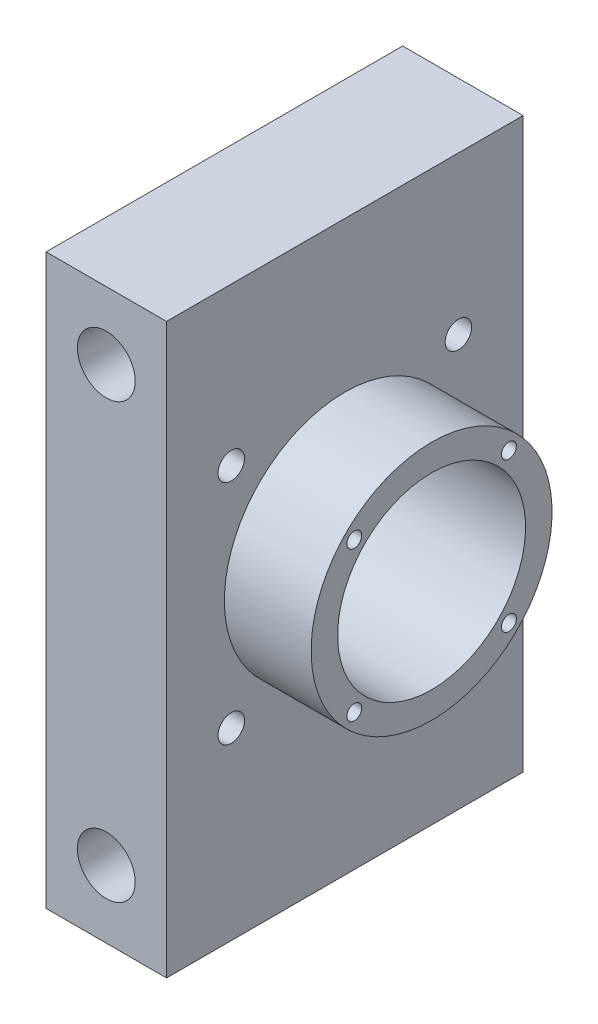
SolidWorks part; units mm, degrees
ref_plane "Front Plane" through (0, 0, 0) normal (0, 0, 1) x (1, 0, 0)
ref_plane "Top Plane" through (0, 0, 0) normal (0, 1, 0) x (1, 0, 0)
ref_plane "Right Plane" through (0, 0, 0) normal (1, 0, 0) x (0, 0, -1)
sketch "Sketch1" plane through (0, 0, 0) normal (0, 0, 1) x (1, 0, 0)
  line L0 (0, 100) -> (0, 85.5)
  line L1 (0, 100) -> (-25, 100)
  line L2 (-25, 100) -> (-25, 0)
  line L3 (-25, 0) -> (0, 0)
  line L4 (6.5355, 52.7939) -> (-58.3851, 52.7939) construction
  line L5 (0, 85.5) -> (-5.5, 85.5)
  line L6 (-5.5, 85.5) -> (-5.5, 92.242)
  line L7 (-5.5, 92.242) -> (-11, 92.242)
  line L8 (-11, 92.242) -> (-11, 13.3459)
  line L9 (-5.5, 20.0879) -> (-5.5, 13.3459)
  line L10 (-5.5, 13.3459) -> (-11, 13.3459)
  line L11 (0, 5.5879) -> (0, 20.0879)
  line L12 (0, 20.0879) -> (-5.5, 20.0879)
  line L13 (0, 0) -> (0, 5.5879)
  point P15 (-11, 52.7939)
  dimension "D1" = 100
  dimension "D2" = 25
  dimension "D3" = 5.5
  dimension "D4" = 5.5
  dimension "D5" = 14.5
extrude "Boss-Extrude1" add sketch "Sketch1" along normal blind 320
sketch "Sketch2" plane through (0, 0, 0) normal (0, 0, -1) x (-1, 0, 0)
  line L0 (0, 100) -> (0, 0)
  line L1 (0, 0) -> (25, 0)
  line L2 (25, 0) -> (25, 100)
  line L3 (25, 100) -> (0, 100)
extrude "Boss-Extrude2" add sketch "Sketch2" along normal blind 50
sketch "Sketch3" plane through (0, 0, 0) normal (1, 0, 0) x (0, 0, -1)
  line L0 (0, 52.7939) -> (50, 52.7939) construction
  line L1 (0, 13.3459) -> (0, 92.242) construction
  line L2 (25, 110.2506) -> (25, -20.6618) construction
  circle A0 centre (25, 52.7939) radius 5
  dimension "D2" = 10
  dimension "D1" = 50
extrude "Cut-Extrude1" cut sketch "Sketch3" against normal through all both and the other way through all
sketch "Sketch4" plane through (0, 100, 0) normal (0, 1, 0) x (1, 0, 0)
  line L0 (-25, -320) -> (-25, -339.2114)
  line L1 (-25, -339.2114) -> (125, -339.2114)
  line L2 (125, -339.2114) -> (125, -320)
  line L3 (125, -320) -> (-25, -320)
  dimension "D1" = 150
extrude "Boss-Extrude3" add sketch "Sketch4" against normal up to surface (100 mm away) up to face at (-12.5, 0, 135)
sketch "Sketch5" plane through (0, 0, 0) normal (0, 1, 0) x (1, 0, 0)
  line L0 (125, -339.2114) -> (125, -209.2114)
  line L1 (125, -209.2114) -> (140, -209.2114)
  line L2 (140, -209.2114) -> (140, -339.2114)
  line L3 (140, -339.2114) -> (127.2454, -339.2114)
  line L4 (125, -339.2114) -> (140, -339.2114)
  dimension "D1" = 130
  dimension "D2" = 15
extrude "Boss-Extrude4" add sketch "Sketch5" along normal up to surface (100 mm away) contours L0 L4 L3 L2 L1 up to face at (33.3333, 100, 203.0705)
sketch "Sketch6" plane through (-25, 0, 0) normal (-1, 0, 0) x (0, 0, 1)
  line L1 (-46.05, 73.8439) -> (-3.95, 73.8439)
  line L2 (-46.05, 73.8439) -> (-46.05, 31.7439)
  line L3 (-46.05, 31.7439) -> (-3.95, 31.7439)
  line L4 (-3.95, 73.8439) -> (-3.95, 31.7439)
  line L5 (-46.05, 73.8439) -> (-3.95, 31.7439) construction
  line L6 (-46.05, 31.7439) -> (-3.95, 73.8439) construction
  point P0 (-25, 52.7939)
  dimension "D1" = 42.1
  dimension "D2" = 42.1
extrude "Cut-Extrude2" cut sketch "Sketch6" against normal blind 10
sketch "Sketch7" plane through (-15, 0, 0) normal (-1, 0, 0) x (0, 0, 1)
  circle A0 centre (-25, 52.7939) radius 11
  dimension "D1" = 22
extrude "Cut-Extrude3" cut sketch "Sketch7" against normal blind 2
sketch "Sketch8" plane through (-25, 0, 0) normal (-1, 0, 0) x (0, 0, 1)
  circle A0 centre (-25, 52.7939) radius 11
extrude "Cut-Extrude4" cut sketch "Sketch8" against normal through all both and the other way through all
sketch "Sketch10" plane through (0, 0, 0) normal (1, 0, 0) x (0, 0, -1)
  circle A0 centre (25, 52.7939) radius 11
  circle A1 centre (25, 52.7939) radius 25
extrude "Boss-Extrude5" add sketch "Sketch10" along normal blind 18
sketch "Sketch11" plane through (0, 0, 0) normal (0, 1, 0) x (1, 0, 0)
  line L0 (-25, -339.2114) -> (-25, -218.2114)
  line L1 (-25, -339.2114) -> (-25, 50) construction
  line L2 (-25, -218.2114) -> (83.7284, -218.2114)
  line L3 (83.7284, -218.2114) -> (83.7284, -190.051)
  line L4 (83.7284, -190.051) -> (162.6734, -190.051)
  line L5 (162.6734, -190.051) -> (162.6734, -339.2114)
  line L6 (162.6734, -339.2114) -> (-25, -339.2114)
  dimension "D1" = 121
extrude "Cut-Extrude6" cut sketch "Sketch11" against normal through all and the other way through all
sketch "Sketch12" plane through (0, 0, 0) normal (0, 1, 0) x (1, 0, 0)
  line L0 (-25, -218.2114) -> (125, -218.2114)
  line L1 (125, -218.2114) -> (125, -203.2114)
  line L2 (125, -203.2114) -> (-25, -203.2114)
  line L3 (-25, -218.2114) -> (-25, 50) construction
  line L4 (-25, -203.2114) -> (-25, -218.2114)
  line L5 (125, -218.2114) -> (140, -218.2114)
  line L6 (140, -218.2114) -> (140, -118.2114)
  line L7 (140, -118.2114) -> (125, -118.2114)
  line L8 (125, -118.2114) -> (125, -203.2114)
  dimension "D1" = 150
  dimension "D2" = 15
  dimension "D3" = 100
  dimension "D4" = 15
extrude "Boss-Extrude6" add sketch "Sketch12" along normal up to surface (100 mm away) contours L2 L4 L0 L1 | L7 L8 L1 L5 L6 up to face at (-12.5, 100, 84.1057)
sketch "Sketch13" plane through (0, 0, 0) normal (0, 1, 0) x (1, 0, 0)
  line L0 (-25, -218.2114) -> (-25, -223.2114)
  line L1 (-25, -223.2114) -> (140, -223.2114)
  line L2 (140, -223.2114) -> (140, -218.2114)
  line L3 (-25, -218.2114) -> (140, -218.2114)
  dimension "D1" = 5
extrude "Boss-Extrude7" add sketch "Sketch13" along normal up to surface (100 mm away) up to face at (60, 100, 122.4085)
sketch "Sketch14" plane through (0, 0, 0) normal (0, 1, 0) x (1, 0, 0)
  line L0 (62.5, -203.2114) -> (62.5, -244.248)
  line L1 (0, -203.2114) -> (125, -203.2114) construction
  line L2 (62.5, -244.248) -> (164.2144, -244.248)
  line L3 (164.2144, -244.248) -> (164.2144, -100.3351)
  line L4 (164.2144, -100.3351) -> (62.5, -100.3351)
  line L5 (62.5, -100.3351) -> (62.5, -203.2114)
extrude "Cut-Extrude7" cut sketch "Sketch14" against normal through all and the other way through all
sketch "Sketch16" plane through (0, 0, 223.2114) normal (0, 0, 1) x (1, 0, 0)
  line L0 (-25, 50) -> (86.2936, 50) construction
  line L1 (-25, 100) -> (-25, 0) construction
  line L2 (0, 100) -> (0, 77.7939)
  line L3 (0, 77.7939) -> (62.5, 77.7939)
  line L4 (62.5, 0) -> (62.5, 100) construction
  line L5 (62.5, 77.7939) -> (62.5, 100)
  line L6 (62.5, 100) -> (0, 100)
  line L7 (62.5, 0) -> (0, 0)
  line L8 (62.5, 22.2061) -> (62.5, 0)
  line L9 (0, 22.2061) -> (62.5, 22.2061)
  line L10 (0, 0) -> (0, 22.2061)
extrude "Cut-Extrude9" cut sketch "Sketch16" against normal through all
sketch "Sketch17" plane through (0, 77.7939, 0) normal (0, 1, 0) x (1, 0, 0)
  line L0 (62.5, -213.2114) -> (0, -213.2114) construction
  line L1 (62.5, -203.2114) -> (62.5, -223.2114) construction
  line L2 (0, -203.2114) -> (0, -223.2114) construction
  line L3 (62.5, -218.2114) -> (62.5, -208.2114)
  line L4 (62.5, -208.2114) -> (0, -208.2114)
  line L5 (0, -223.2114) -> (0, 50) construction
  line L6 (0, -208.2114) -> (0, -218.2114)
  line L7 (0, -213.2114) -> (62.5, -213.2114)
  line L8 (62.5, -218.2114) -> (0, -218.2114)
  line M5 (0, -203.2114) -> (0, -223.2114)
  line M7 (62.5, -223.2114) -> (62.5, -203.2114)
  dimension "D1" = 5
extrude "Boss-Extrude8" add sketch "Sketch17" along normal blind 15 contours L7 L3 L4 M5 | L8 L7 L6 M7
sketch "Sketch18" plane through (0, 22.2061, 0) normal (0, -1, 0) x (1, 0, 0)
  line L0 (0, 213.2114) -> (62.5, 213.2114) construction
  line L1 (0, 203.2114) -> (0, 223.2114) construction
  line L2 (62.5, 223.2114) -> (62.5, 203.2114) construction
  line L3 (62.5, 207.5301) -> (62.5, 218.8926)
  line L4 (62.5, 218.8926) -> (0, 218.8926)
  line L5 (0, 223.2114) -> (0, -50) construction
  line L6 (0, 218.8926) -> (0, 207.5301)
  line L7 (62.5, 207.5301) -> (0, 207.5301)
extrude "Boss-Extrude9" add sketch "Sketch18" along normal blind 15
sketch "Sketch19" plane through (0, 0, 223.2114) normal (0, 0, 1) x (1, 0, 0)
  line L1 (-25, 100) -> (0, 100)
  line L2 (-25, 100) -> (-25, 0)
  line L3 (-25, 0) -> (0, 0)
  line L4 (0, 100) -> (0, 0)
extrude "Boss-Extrude11" add sketch "Sketch19" along normal blind 9
sketch "Sketch20" plane through (62.5, 0, 0) normal (1, 0, 0) x (0, 0, -1)
  line L0 (-223.2114, 50) -> (-203.2114, 50) construction
  line L1 (-223.2114, 22.2061) -> (-223.2114, 77.7939) construction
  line L2 (-203.2114, 77.7939) -> (-203.2114, 22.2061) construction
  circle A0 centre (-213.2114, 50) radius 5
  dimension "D1" = 10
extrude "Cut-Extrude10" cut sketch "Sketch20" against normal up to surface (62.5 mm away) up to face at (0, 50.9313, 134.5576)
sketch "Sketch21" plane through (62.5, 0, 0) normal (1, 0, 0) x (0, 0, -1)
  circle A0 centre (-213.2114, 50) radius 6
  dimension "D1" = 12
extrude "Cut-Extrude11" cut sketch "Sketch21" against normal up to surface (62.5 mm away) up to face at (0, 50.9313, 134.5576)
sketch "Sketch22" plane through (62.5, 0, 0) normal (1, 0, 0) x (0, 0, -1)
  line L0 (-203.2114, 13.3459) -> (-203.2114, 92.242) construction
  line L1 (-204.6114, 45.0348) -> (-204.6114, 54.9652)
  line L2 (-204.6114, 54.9652) -> (-213.2114, 59.9304)
  line L3 (-213.2114, 59.9304) -> (-221.8114, 54.9652)
  line L4 (-221.8114, 54.9652) -> (-221.8114, 45.0348)
  line L5 (-221.8114, 45.0348) -> (-213.2114, 40.0696)
  line L6 (-213.2114, 40.0696) -> (-204.6114, 45.0348)
  circle A0 centre (-213.2114, 50) radius 8.6
  circle A1 centre (-213.2114, 50) radius 8.6 construction
  dimension "D1" = 17.2
extrude "Cut-Extrude12" cut sketch "Sketch22" against normal blind 7 contours L1 L2 L3 L4 L5 L6
sketch "Sketch23" plane through (0, 0, 0) normal (1, 0, 0) x (0, 0, -1)
  line L1 (50, 100) -> (0, 100)
  line L2 (50, 100) -> (50, 0)
  line L3 (50, 0) -> (0, 0)
  line L4 (0, 100) -> (0, 0)
extrude "Cut-Extrude14" cut sketch "Sketch23" against normal through all both and the other way through all flip side to cut
sketch "Sketch24" plane through (0, 0, 0) normal (0, 0, 1) x (1, 0, 0)
  line L0 (-12.5, 100) -> (-12.5, 0) construction
  line L1 (-25, 100) -> (0, 100) construction
  line L2 (-25, 0) -> (0, 0) construction
  line L3 (-12.5, 50) -> (-52.9722, 50) construction
  circle A0 centre (-12.5, 90) radius 6
  circle A1 centre (-12.5, 10) radius 6
  dimension "D1" = 12
  dimension "D2" = 10
extrude "Cut-Extrude15" cut sketch "Sketch24" against normal through all both and the other way through all
sketch "Sketch25" plane through (0, 0, 0) normal (0, 0, 1) x (1, 0, 0)
  line L0 (-25, 50) -> (-78.9909, 50) construction
  line L1 (-25, 100) -> (-25, 0) construction
  line L2 (-25, 100) -> (-25, 105)
  line L3 (-25, 105) -> (0, 105)
  line L4 (0, 105) -> (0, 100)
  line L5 (0, 100) -> (-25, 100)
  line L6 (-25, 0) -> (-25, -5)
  line L7 (0, -5) -> (0, 0)
  line L8 (-25, -5) -> (0, -5)
  line L9 (0, 0) -> (-25, 0)
  dimension "D1" = 5
extrude "Boss-Extrude12" add sketch "Sketch25" against normal up to surface (50 mm away) up to face at (-18.5, 10, -50)
sketch "Sketch26" plane through (0, 0, 0) normal (0, 0, 1) x (1, 0, 0)
  line L0 (-25, 50) -> (-65.909, 50) construction
  line L1 (-25, 105) -> (-25, -5) construction
  line L2 (0, -5) -> (0, -9)
  line L3 (-25, 105) -> (0, 105)
  line L4 (-25, 105) -> (-25, 109)
  line L5 (-25, 109) -> (0, 109)
  line L6 (0, 105) -> (0, 109)
  line L7 (-25, -5) -> (0, -5)
  line L8 (-25, -9) -> (0, -9)
  line L9 (-25, -5) -> (-25, -9)
  dimension "D1" = 4
extrude "Boss-Extrude13" add sketch "Sketch26" against normal up to surface (50 mm away) up to face at (-18.5, 10, -50)
sketch "Sketch27" plane through (-15, 0, 0) normal (-1, 0, 0) x (0, 0, 1)
  line L1 (-41.0453, 68.2939) -> (-8.9547, 68.2939)
  line L2 (-41.0453, 68.2939) -> (-41.0453, 37.2939)
  line L3 (-41.0453, 37.2939) -> (-8.9547, 37.2939)
  line L4 (-8.9547, 68.2939) -> (-8.9547, 37.2939)
  line L5 (-41.0453, 68.2939) -> (-8.9547, 37.2939) construction
  line L6 (-41.0453, 37.2939) -> (-8.9547, 68.2939) construction
  circle A0 centre (-8.9547, 68.2939) radius 1.55
  circle A1 centre (-41.0453, 68.2939) radius 1.55
  circle A2 centre (-41.0453, 37.2939) radius 1.55
  circle A3 centre (-8.9547, 37.2939) radius 1.55
  point P0 (-25, 52.7939)
  dimension "D2" = 3.1
  dimension "D1" = 31
extrude "Cut-Extrude17" cut sketch "Sketch27" against normal through all both and the other way through all contours A1 | A0 | A3 | A2
sketch "Sketch28" plane through (0, 0, 0) normal (0, 0, 1) x (1, 0, 0)
  circle A0 centre (-12.5, 90) radius 6
  circle A1 centre (-12.5, 10) radius 6
extrude "Boss-Extrude14" add sketch "Sketch28" against normal up to surface (50 mm away) up to face at (-18.5, 10, -50)
sketch "Sketch29" plane through (0, 0, 0) normal (0, 0, 1) x (1, 0, 0)
  line L0 (-12.5, 109) -> (-12.5, -9) construction
  line L1 (0, 109) -> (-25, 109) construction
  line L2 (-25, -9) -> (0, -9) construction
  line L3 (-12.5, 50) -> (52.4239, 50) construction
  circle A0 centre (-12.5, 99) radius 5
  circle A1 centre (-12.5, 1) radius 5
  dimension "D1" = 10
  dimension "D2" = 10
extrude "Cut-Extrude18" cut sketch "Sketch29" against normal through all
sketch "Sketch30" plane through (0, 0, 0) normal (0, 0, 1) x (1, 0, 0)
  circle A0 centre (-12.5, 99) radius 5
  circle A1 centre (-12.5, 1) radius 5
extrude "Boss-Extrude15" add sketch "Sketch30" against normal up to surface (50 mm away) up to face at (-17.5, 1, -50)
sketch "Sketch31" plane through (0, 0, 0) normal (0, 0, 1) x (1, 0, 0)
  line L0 (-12.5, 109) -> (-12.5, -13.5533) construction
  line L1 (0, 109) -> (-25, 109) construction
  line L2 (-12.5, 47.7233) -> (-59.9303, 47.7233) construction
  line L3 (-25, -9) -> (0, -9) construction
  circle A0 centre (-12.5, 95) radius 6
  circle A1 centre (-12.5, 5) radius 6
  dimension "D1" = 12
  dimension "D2" = 14
  dimension "D3" = 12
  dimension "D4" = 14
extrude "Cut-Extrude19" cut sketch "Sketch31" against normal through all
sketch "Sketch32" plane through (-25, 0, 0) normal (-1, 0, 0) x (0, 0, 1)
  line L0 (-25, 109) -> (-25, -17.1239) construction
  line L1 (-50, 109) -> (0, 109) construction
  line L2 (0, 109) -> (12, 109)
  line L3 (12, 109) -> (12, -9)
  line L4 (12, -9) -> (0, -9)
  line L5 (0, -9) -> (0, 109)
  line L6 (-50, -9) -> (-50, 109)
  line L7 (-62, -9) -> (-50, -9)
  line L8 (-62, 109) -> (-62, -9)
  line L9 (-50, 109) -> (-62, 109)
  dimension "D1" = 12
extrude "Boss-Extrude17" add sketch "Sketch32" against normal up to surface (25 mm away) up to face at (0, 87.147, -25)
sketch "Sketch35" plane through (-25, 0, 0) normal (-1, 0, 0) x (0, 0, 1)
  line L1 (-53.5, 81.2939) -> (3.5, 81.2939)
  line L2 (-53.5, 81.2939) -> (-53.5, 24.2939)
  line L3 (-53.5, 24.2939) -> (3.5, 24.2939)
  line L4 (3.5, 81.2939) -> (3.5, 24.2939)
  line L5 (-53.5, 81.2939) -> (3.5, 24.2939) construction
  line L6 (-53.5, 24.2939) -> (3.5, 81.2939) construction
  point P0 (-25, 52.7939)
  dimension "D1" = 57
  dimension "D2" = 57
extrude "Cut-Extrude20" cut sketch "Sketch35" against normal up to surface (10 mm away) up to face at (-15, 66.7439, -8.9547)
sketch "Sketch36" plane through (-15, 0, 0) normal (-1, 0, 0) x (0, 0, 1)
  circle A0 centre (-25, 52.7939) radius 19.5
  dimension "D1" = 39
extrude "Cut-Extrude21" cut sketch "Sketch36" against normal through all
sketch "Sketch37" plane through (-15, 0, 0) normal (-1, 0, 0) x (0, 0, 1)
  line L1 (-48.57, 76.3639) -> (-1.43, 76.3639)
  line L2 (-48.57, 76.3639) -> (-48.57, 29.2239)
  line L3 (-48.57, 29.2239) -> (-1.43, 29.2239)
  line L4 (-1.43, 76.3639) -> (-1.43, 29.2239)
  line L5 (-48.57, 76.3639) -> (-1.43, 29.2239) construction
  line L6 (-48.57, 29.2239) -> (-1.43, 76.3639) construction
  circle A0 centre (-48.57, 76.3639) radius 2.75
  circle A1 centre (-1.43, 76.3639) radius 2.75
  circle A2 centre (-1.43, 29.2239) radius 2.75
  circle A3 centre (-48.57, 29.2239) radius 2.75
  point P0 (-25, 52.7939)
  dimension "D3" = 5.5
  dimension "D1" = 47.14
  dimension "D2" = 47.14
extrude "Cut-Extrude23" cut sketch "Sketch37" against normal through all contours A0 | A1 | A2 | A3
sketch "Sketch38" plane through (0, 0, 12) normal (0, 0, 1) x (1, 0, 0)
  line L0 (-12.5, 109) -> (-12.5, -9) construction
  line L1 (0, 109) -> (-25, 109) construction
  line L2 (0, -9) -> (-25, -9) construction
  circle A0 centre (-12.5, 95) radius 6
  circle A1 centre (-12.5, 5) radius 6
  dimension "D1" = 12
  dimension "D2" = 12
  dimension "D4" = 14
  dimension "D3" = 14
extrude "Cut-Extrude24" cut sketch "Sketch38" against normal through all both and the other way through all
sketch "Sketch39" plane through (-25, 0, 0) normal (-1, 0, 0) x (0, 0, 1)
  line L1 (-53.75, 24.0439) -> (3.75, 24.0439)
  line L2 (-53.75, 24.0439) -> (-53.75, 81.5439)
  line L3 (-53.75, 81.5439) -> (3.75, 81.5439)
  line L4 (3.75, 24.0439) -> (3.75, 81.5439)
  line L5 (-53.75, 24.0439) -> (3.75, 81.5439) construction
  line L6 (-53.75, 81.5439) -> (3.75, 24.0439) construction
  point P0 (-25, 52.7939)
  dimension "D1" = 57.5
  dimension "D2" = 57.5
extrude "Cut-Extrude25" cut sketch "Sketch39" against normal up to surface (10 mm away) up to face at (-15, 73.6139, -1.43)
sketch "Sketch41" plane through (-15, 0, 0) normal (-1, 0, 0) x (0, 0, 1)
  line L1 (-53.75, 24.0439) -> (3.75, 24.0439)
  line L2 (-53.75, 24.0439) -> (-53.75, 81.5439)
  line L3 (-53.75, 81.5439) -> (3.75, 81.5439)
  line L4 (3.75, 24.0439) -> (3.75, 81.5439)
  line L5 (-53.75, 24.0439) -> (3.75, 81.5439) construction
  line L6 (-53.75, 81.5439) -> (3.75, 24.0439) construction
  point P0 (-25, 52.7939)
extrude "Cut-Extrude26" cut sketch "Sketch41" against normal blind 5
